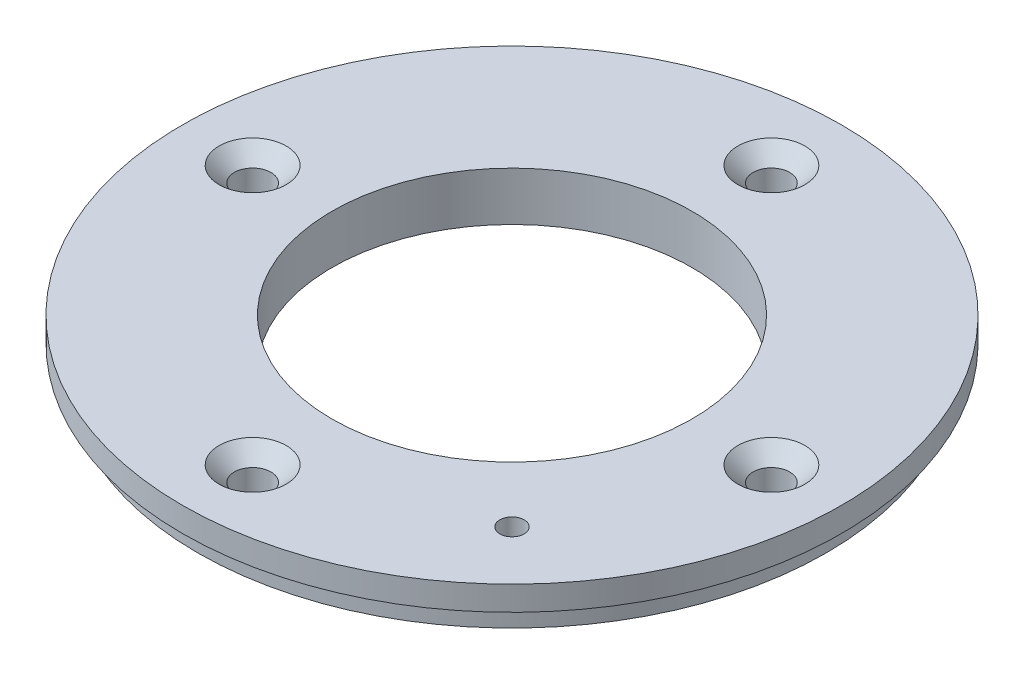
SolidWorks part; units mm, degrees
ref_plane "Спереди" through (0, 0, 0) normal (0, 0, 1) x (1, 0, 0)
ref_plane "Сверху" through (0, 0, 0) normal (0, 1, 0) x (1, 0, 0)
ref_plane "Справа" through (0, 0, 0) normal (1, 0, 0) x (0, 0, -1)
sketch "Эскиз1" plane through (0, 0, 0) normal (0, 1, 0) x (1, 0, 0)
  circle A0 centre (0, 0) radius 51.5
  dimension "D1" = 103
extrude "Бобышка-Вытянуть1" add sketch "Эскиз1" along normal blind 4
sketch "Эскиз2" plane through (0, 4, 0) normal (0, 1, 0) x (1, 0, 0)
  circle A0 centre (0, 0) radius 54
  dimension "D1" = 108
extrude "Бобышка-Вытянуть2" add sketch "Эскиз2" along normal blind 4
sketch "Эскиз3" plane through (0, 8, 0) normal (0, 1, 0) x (1, 0, 0)
  circle A0 centre (0, 0) radius 29.5
  dimension "D1" = 59
extrude "Вырез-Вытянуть1" cut sketch "Эскиз3" against normal blind 10
sketch "Эскиз4" plane through (0, 8, 0) normal (0, 1, 0) x (1, 0, 0)
  circle A0 centre (0, 0) radius 42.5 construction
  circle A1 centre (0, 42.5) radius 3
  circle A2 centre (-42.5, 0) radius 3
  circle A3 centre (0, -42.5) radius 3
  circle A4 centre (42.5, 0) radius 3
  dimension "D1" = 85
  dimension "D2" = 6
  dimension "D3" = 6
  dimension "D4" = 6
  dimension "D5" = 6
extrude "Вырез-Вытянуть2" cut sketch "Эскиз4" against normal blind 10
chamfer "Фаска2" distance 2.5 angle 45 4 edges at (0, 8, 45.5) (42.5, 8, 3) (0, 8, -39.5) (-42.5, 8, 3)
sketch "Эскиз5" plane through (0, 8, 0) normal (0, 1, 0) x (1, 0, 0)
  line L0 (0, 0) -> (33.847, -33.847) construction
  line L1 (0, 0) -> (42.5, 0) construction
  line L2 (0, 0) -> (-42.5, 0) construction
  line L3 (-42.5, 0) -> (0, 42.5) construction
  line L4 (0, 42.5) -> (0, -42.5) construction
  circle A0 centre (30.052, -30.052) radius 2
  circle A1 centre (0, 0) radius 42.5 construction
  dimension "D2" = 4
  dimension "D1" = 45
extrude "Вырез-Вытянуть3" cut sketch "Эскиз5" against normal blind 10
